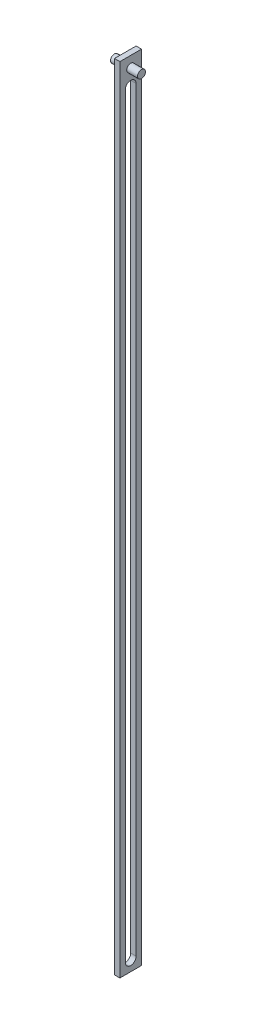
SolidWorks part; units mm, degrees
ref_plane "Front Plane" through (0, 0, 0) normal (0, 0, 1) x (1, 0, 0)
ref_plane "Top Plane" through (0, 0, 0) normal (0, 1, 0) x (1, 0, 0)
ref_plane "Right Plane" through (0, 0, 0) normal (1, 0, 0) x (0, 0, -1)
sketch "Sketch1" plane through (0, 0, 0) normal (1, 0, 0) x (0, 0, -1)
  line L0 (-4.0811, -23.9769) -> (-4.0811, 420.5231) construction
  line L1 (-10.4311, -30.3269) -> (2.2689, -30.3269)
  line L2 (-10.4311, -30.3269) -> (-10.4311, 426.8731)
  line L3 (-10.4311, 426.8731) -> (2.2689, 426.8731)
  line L4 (2.2689, -30.3269) -> (2.2689, 426.8731)
  line L5 (-10.4311, -30.3269) -> (2.2689, 426.8731) construction
  line L6 (-10.4311, 426.8731) -> (2.2689, -30.3269) construction
  line L7 (-7.2561, -23.9769) -> (-7.2561, 420.5231)
  line L8 (-0.9061, -23.9769) -> (-0.9061, 420.5231)
  arc A0 (-7.2561, -23.9769) -> (-0.9061, -23.9769) centre (-4.0811, -23.9769) ccw
  arc A1 (-0.9061, 420.5231) -> (-7.2561, 420.5231) centre (-4.0811, 420.5231) ccw
  point P0 (-4.0811, 198.2731)
  point P7 (-4.0811, 198.2731)
  point P12 (0, 0)
extrude "Boss-Extrude1" add sketch "Sketch1" along normal blind 3.175
sketch "Sketch2" plane through (0, 426.8731, 0) normal (0, 1, 0) x (1, 0, 0)
  line L1 (3.175, -10.4311) -> (0, -10.4311)
  line L2 (3.175, -10.4311) -> (3.175, 2.2689)
  line L3 (3.175, 2.2689) -> (0, 2.2689)
  line L4 (0, -10.4311) -> (0, 2.2689)
extrude "Boss-Extrude2" add sketch "Sketch2" along normal blind 9.525
sketch "Sketch3" plane through (3.175, 0, 0) normal (1, 0, 0) x (0, 0, -1)
  line L0 (2.2689, -30.3269) -> (2.2689, 436.3981) construction
  line L1 (-10.4311, 436.3981) -> (2.2689, 436.3981) construction
  circle A0 centre (-4.0811, 430.0481) radius 2.3373
  dimension "D1" = 6.35
  dimension "D2" = 6.35
extrude "Boss-Extrude3" add sketch "Sketch3" along normal blind 6.35 and the other way blind 9.525
